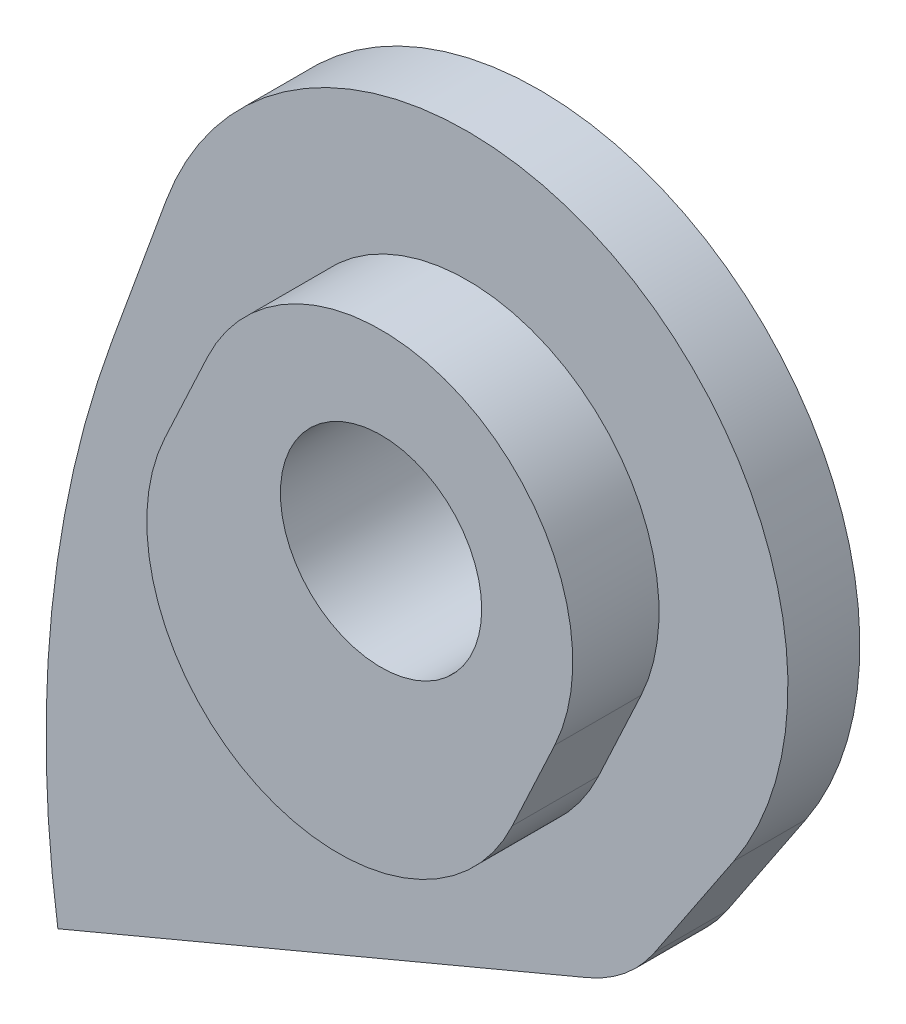
SolidWorks part; units mm, degrees
ref_plane "Front Plane" through (0, 0, 0) normal (0, 0, 1) x (1, 0, 0)
ref_plane "Top Plane" through (0, 0, 0) normal (0, 1, 0) x (1, 0, 0)
ref_plane "Right Plane" through (0, 0, 0) normal (1, 0, 0) x (0, 0, -1)
sketch "Sketch6" plane through (0, 0, 0) normal (0, 0, 1) x (1, 0, 0)
  line L0 (0, 0) -> (40.1809, 0) construction
  line L1 (0, 0) -> (35.507, 92.499) construction
  line L2 (19.3519, 50.4133) -> (0.4719, 63.0164) construction
  line L3 (19.3519, 50.4133) -> (-36.1025, 71.7003) construction
  dimension "D1" = 69
  dimension "D2" = 54
  dimension "D3" = 22.7
  dimension "D4" = 5
sketch "Sketch3" plane through (0, 0, 0) normal (0, 0, 1) x (1, 0, 0)
  line L0 (24.1743, 72.523) -> (120.8717, 72.523) construction
  line L6 (11.8164, 60.2529) -> (11.7284, 60.3116)
  line L7 (7.3748, 53.5992) -> (5.9136, 54.5745)
  line L8 (19.3519, 50.4133) -> (0.4719, 63.0164) construction
  line L9 (-6.1719, 82.4206) -> (-7.2903, 79.3479)
  line L10 (19.3519, 50.4133) -> (13.2479, 41.2693) construction
  line L11 (19.3519, 50.4133) -> (31.6629, 68.8558) construction
  line L12 (4.0204, 73.9337) -> (5.6789, 76.4182)
  line L14 (0.1147, 80.1325) -> (27.1455, 62.0885) construction
  line L15 (0.1147, 80.1325) -> (-7.2903, 79.3479) construction
  line L16 (0.1147, 80.1325) -> (0.1147, 91.1913) construction
  line L17 (0.1147, 80.1325) -> (-6.1719, 82.4206) construction
  arc A0 (13.4996, 47.0498) -> (20.2139, 57.1081) centre (19.3519, 50.4133) ccw
  arc A1 (20.2139, 57.1081) -> (11.8164, 60.2529) centre (22.7223, 76.5904) cw
  arc A2 (13.4996, 47.0498) -> (7.3748, 53.5992) centre (-3.5311, 37.2616) ccw
  arc A3 (11.7284, 60.3116) -> (6.8662, 65.9311) centre (19.4923, 71.9424) cw
  arc A4 (-6.1719, 82.4206) -> (5.6789, 76.4182) centre (0.1147, 80.1325) cw
  arc A5 (6.8662, 65.9311) -> (4.9012, 68.3908) centre (0.6246, 62.9595) ccw
  arc A6 (4.9012, 68.3908) -> (4.0204, 73.9337) centre (7.4585, 71.6386) cw
  arc A7 (5.9136, 54.5745) -> (0.4148, 56.2666) centre (0.3298, 46.2096) ccw
  arc A10 (0.4148, 56.2666) -> (-5.2798, 59.4837) centre (0.4719, 63.0164) cw
  circle A12 centre (19.3519, 50.4133) radius 2.75
  circle A13 centre (0.4719, 63.0164) radius 2.75
  circle A17 centre (0.1147, 80.1325) radius 2.1
  arc A18 (-7.2903, 79.3479) -> (-5.2798, 59.4837) centre (14.2795, 71.4971) ccw
  dimension "D1" = 5.5
  dimension "D2" = 5.5
  dimension "D3" = 4
  dimension "D5" = 4
  dimension "D6" = 4
  dimension "D4" = 4.2
  dimension "D17" = 70
  dimension "D18" = 3.27
  dimension "D14" = 6.69
  dimension "D7" = 3
  dimension "D8" = 4
  dimension "D9" = 3
  dimension "D10" = 4
  dimension "D11" = 19
  dimension "D12" = 19
  dimension "D13" = 22
  dimension "D15" = 32.5
  dimension "D16" = 14
extrude "Boss-Extrude2" add sketch "Sketch3" along normal blind 11
sketch "Sketch13" plane through (0, 0, 0) normal (0, 0, -1) x (-1, 0, 0)
  line L0 (-5.6789, 76.4182) -> (-4.0204, 73.9337)
  line L1 (-2.6258, 72.7829) -> (8.4277, 68.1397)
  line L2 (6.1719, 82.4206) -> (7.2903, 79.3479)
  arc A0 (-5.6789, 76.4182) -> (6.1719, 82.4206) centre (-0.1147, 80.1325) cw
  arc A1 (6.1719, 82.4206) -> (-5.6789, 76.4182) centre (-0.1147, 80.1325) ccw construction
  arc A2 (-4.0204, 73.9337) -> (-2.6258, 72.7829) centre (-1.4106, 75.6758) ccw
  arc A3 (5.2798, 59.4837) -> (7.2903, 79.3479) centre (-14.2795, 71.4971) ccw construction
  arc A4 (8.4277, 68.1397) -> (7.2903, 79.3479) centre (-14.2795, 71.4971) ccw
extrude "Boss-Extrude4" add sketch "Sketch13" along normal blind 1.5
sketch "Sketch12" plane through (0, 0, -1.5) normal (0, 0, -1) x (-1, 0, 0)
  line L0 (8.0136, 76.9658) -> (4.9242, 69.6114)
  line L4 (4.9242, 69.6114) -> (8.4277, 68.1397)
  line L5 (-2.6258, 72.7829) -> (8.4277, 68.1397) construction
  line L8 (-2.6258, 72.7829) -> (8.4277, 68.1397) construction
  arc A0 (8.0136, 76.9658) -> (8.4277, 68.1397) centre (-14.2795, 71.4971) cw
  arc A1 (5.2798, 59.4837) -> (8.4277, 68.1397) centre (-14.2795, 71.4971) ccw construction
  dimension "D1" = 3.8
  dimension "D2" = 90
extrude "Boss-Extrude3" add sketch "Sketch12" along normal blind 3
sketch "Sketch14" plane through (0, 0, 0) normal (0, 1, 0) x (1, 0, 0)
  line L0 (19.3519, 0) -> (-36.1025, 0) construction
  line L1 (-15.2308, 0) -> (32.0549, 0)
  line L2 (-15.2308, 0) -> (-15.2308, -12.5955)
  line L3 (-15.2308, -12.5955) -> (32.0549, -12.5955)
  line L4 (32.0549, 0) -> (32.0549, -12.5955)
extrude "Cut-Extrude1" cut sketch "Sketch14" along normal through all
sketch "Sketch16" plane through (0, 0, 0) normal (0, 0, 1) x (1, 0, 0)
  line L0 (0.1147, 80.1325) -> (-0.7728, 78.2293) construction
  line L1 (3.7399, 78.4421) -> (2.8524, 76.5388)
  line L2 (-3.5105, 81.823) -> (-4.398, 79.9198)
  line L3 (0.1147, 80.1325) -> (0.1147, 75.6752) construction
  arc A0 (3.7399, 78.4421) -> (-3.5105, 81.823) centre (0.1147, 80.1325) ccw
  arc A1 (-4.398, 79.9198) -> (2.8524, 76.5388) centre (-0.7728, 78.2293) ccw
  point P3 (-0.3291, 79.1809)
  dimension "D1" = 4
  dimension "D2" = 25
  dimension "D3" = 2.1
extrude "Boss-Extrude5" add sketch "Sketch16" along normal blind 1.8
sketch "Sketch15" plane through (0, 0, 1.8) normal (0, 0, 1) x (1, 0, 0)
  circle A0 centre (0.1147, 80.1325) radius 2.1
  dimension "D1" = 4.2
extrude "Cut-Extrude2" cut sketch "Sketch15" against normal through all
